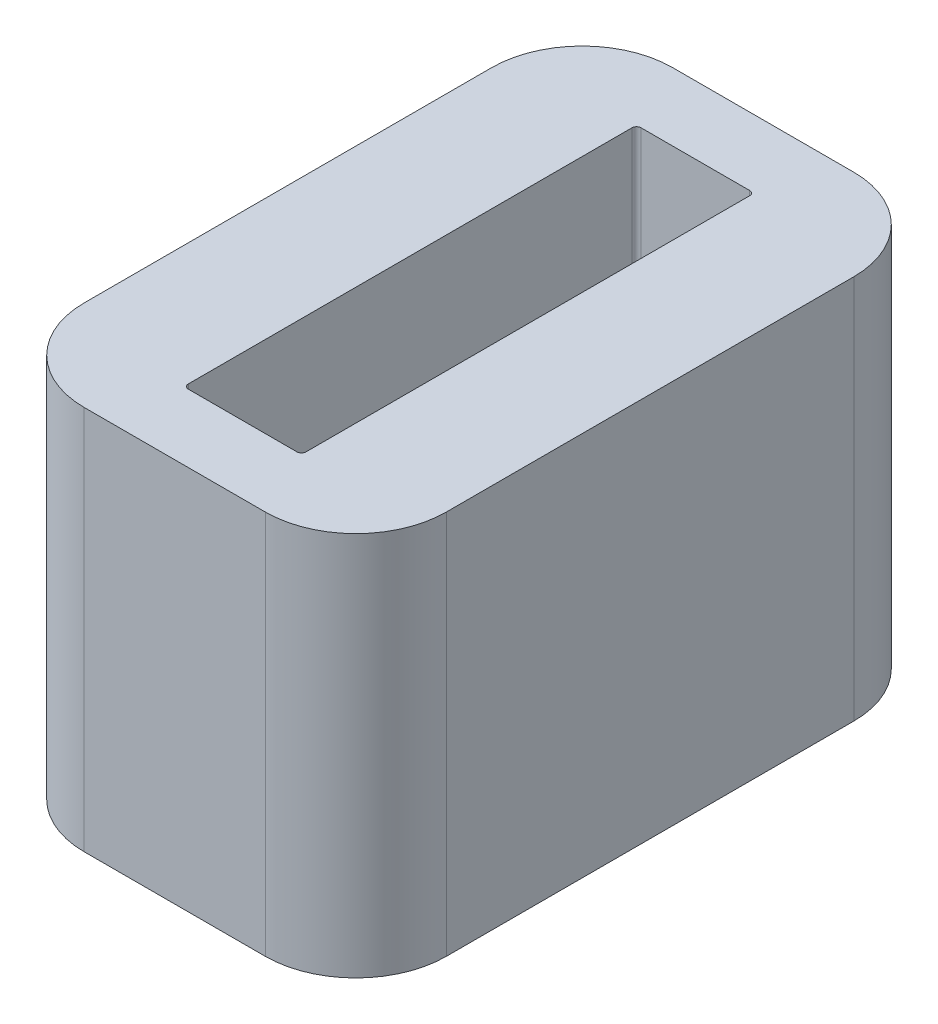
SolidWorks part; units mm, degrees
material "Copper"
ref_plane "Front Plane" through (0, 0, 0) normal (0, 0, 1) x (1, 0, 0)
ref_plane "Top Plane" through (0, 0, 0) normal (0, 1, 0) x (1, 0, 0)
ref_plane "Right Plane" through (0, 0, 0) normal (1, 0, 0) x (0, 0, -1)
sketch "Sketch1" plane through (0, 97.2795, 0) normal (0, 1, 0) x (1, 0, 0)
  line L0 (92.0978, 84.0094) -> (86.0478, 64.2094) construction
  line L1 (86.0478, 64.2094) -> (92.0978, 64.2094) construction
  line L2 (86.0478, 64.2094) -> (86.0478, 84.0094) construction
  line L3 (86.0478, 84.0094) -> (92.0978, 84.0094) construction
  line L4 (92.0978, 64.2094) -> (92.0978, 84.0094) construction
  line L6 (87.0728, 67.6094) -> (91.0728, 67.6094)
  line L7 (85.0728, 69.6094) -> (85.0728, 78.6094)
  line L8 (87.0728, 80.6094) -> (91.0728, 80.6094)
  line L9 (93.0728, 69.6094) -> (93.0728, 78.6094)
  line L10 (85.0728, 67.6094) -> (93.0728, 80.6094) construction
  line L11 (85.0728, 80.6094) -> (93.0728, 67.6094) construction
  line L12 (87.7728, 69.1094) -> (90.3728, 69.1094)
  line L13 (87.7728, 69.1094) -> (87.7728, 79.1094)
  line L14 (87.7728, 79.1094) -> (90.3728, 79.1094)
  line L15 (90.3728, 69.1094) -> (90.3728, 79.1094)
  line L16 (87.7728, 69.1094) -> (90.3728, 79.1094) construction
  line L17 (87.7728, 79.1094) -> (90.3728, 69.1094) construction
  arc A0 (87.0728, 67.6094) -> (85.0728, 69.6094) centre (87.0728, 69.6094) cw
  arc A1 (91.0728, 67.6094) -> (93.0728, 69.6094) centre (91.0728, 69.6094) ccw
  arc A2 (91.0728, 80.6094) -> (93.0728, 78.6094) centre (91.0728, 78.6094) cw
  arc A3 (85.0728, 78.6094) -> (87.0728, 80.6094) centre (87.0728, 78.6094) cw
  point P7 (89.0728, 74.1094)
  point P23 (89.0728, 74.1094)
  dimension "D3" = 2
  dimension "D1" = 8
  dimension "D2" = 13
  dimension "D4" = 2.6
  dimension "D5" = 10
extrude "Coil" add sketch "Sketch1" against normal blind 8.5 from offset 0.7 offset against normal yes
fillet "Fillet1" radius 0.1 4 edges at (90.3728, 92.3295, -69.1094) (87.7728, 92.3295, -69.1094) (87.7728, 92.3295, -79.1094) (90.3728, 92.3295, -79.1094)
